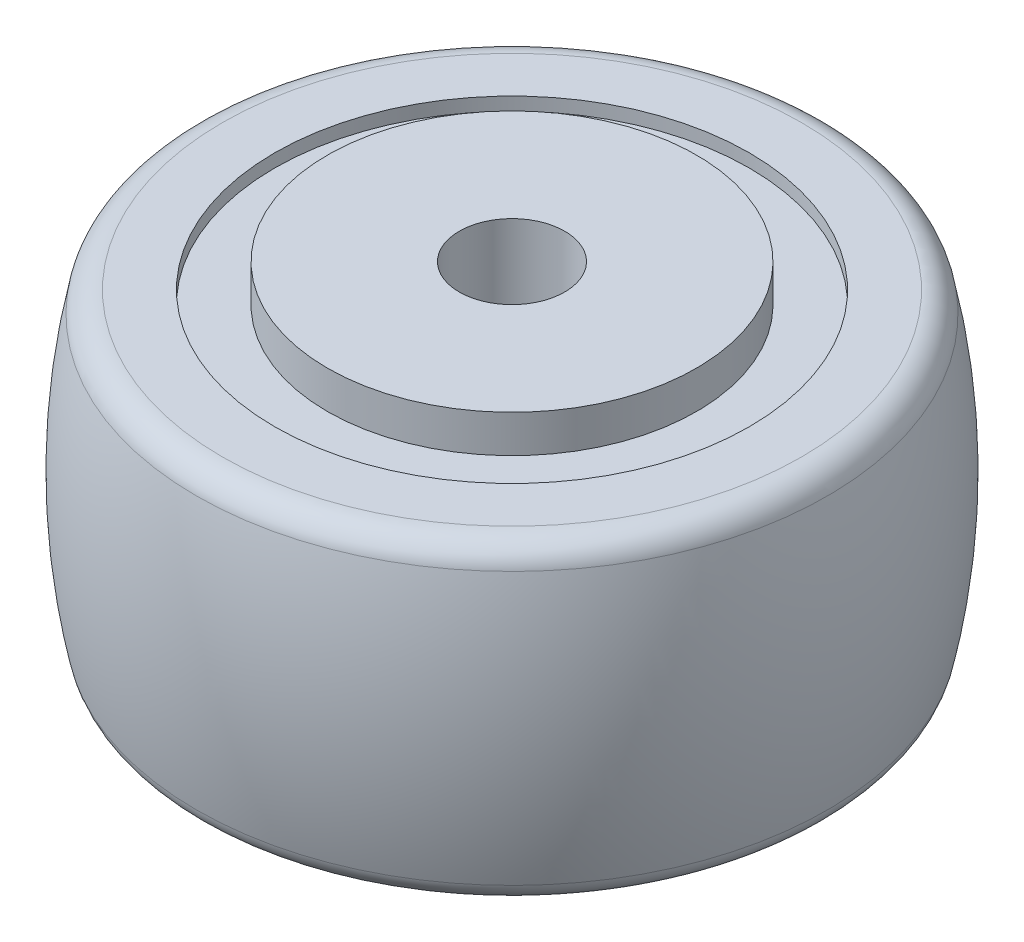
SolidWorks part; units mm, degrees
ref_plane "前视基准面" through (0, 0, 0) normal (0, 0, 1) x (1, 0, 0)
ref_plane "上视基准面" through (0, 0, 0) normal (0, 1, 0) x (1, 0, 0)
ref_plane "右视基准面" through (0, 0, 0) normal (1, 0, 0) x (0, 0, -1)
other "Configuration Table"
ref_plane "基准面1" through (0, 0, 0) normal (0, 0, -1) x (-1, 0, 0)
sketch "草图1" plane through (0, 0, 0) normal (0, 0, -1) x (-1, 0, 0)
  line L0 (-14, -13.75) -> (-4, -13.75)
  line L1 (-4, -13.75) -> (-4, 13.75)
  line L2 (-4, 13.75) -> (-14, 13.75)
  line L3 (-14, 13.75) -> (-14, 10.9)
  line L4 (-14, 10.9) -> (-18, 10.9)
  line L5 (-18, 10.9) -> (-18, 11.9)
  line L6 (-18, 11.9) -> (-21.968, 11.9)
  line L7 (-21.968, -11.9) -> (-18, -11.9)
  line L8 (-18, -11.9) -> (-18, -10.9)
  line L9 (-18, -10.9) -> (-14, -10.9)
  line L10 (-14, -10.9) -> (-14, -13.75)
  line L11 (0, -13.75) -> (0, 13.75) construction
  arc A0 (-21.968, 11.9) -> (-23.925, 10.3125) centre (-21.968, 9.9) ccw
  arc A1 (-23.925, 10.3125) -> (-23.925, -10.3125) centre (25, 0) ccw
  arc A2 (-23.925, -10.3125) -> (-21.968, -11.9) centre (-21.968, -9.9) ccw
revolve "旋转1" add sketch "草图1" angle 360 about L11
